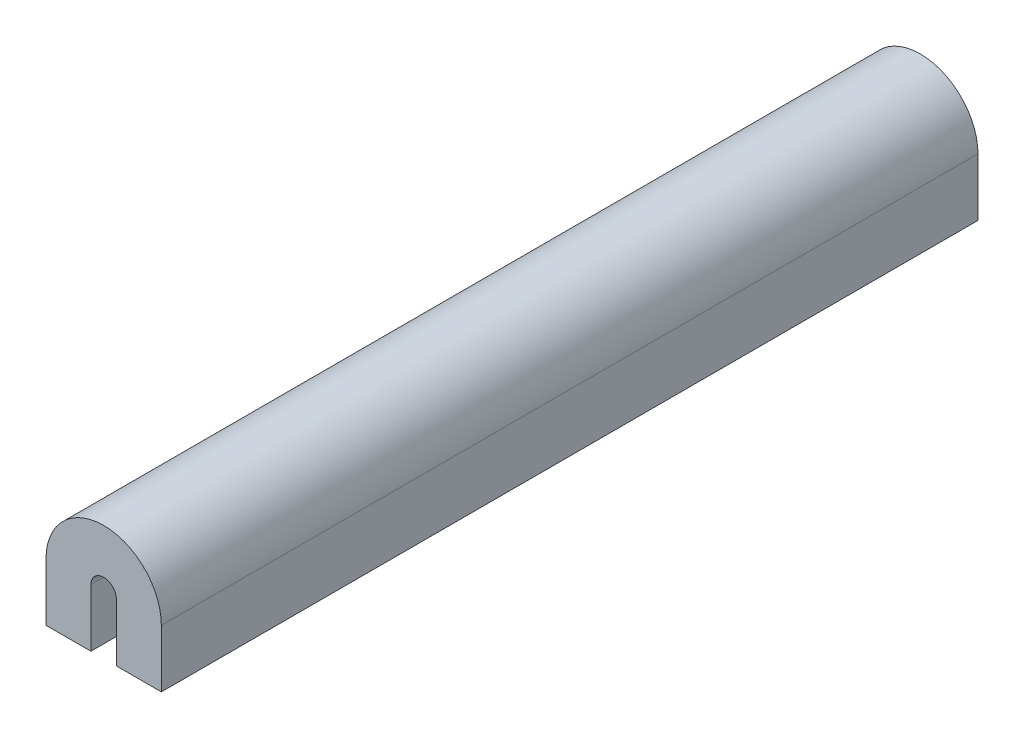
SolidWorks part; units mm, degrees
material "Rubber"
ref_plane "Front" through (0, 0, 0) normal (0, 0, 1) x (1, 0, 0)
ref_plane "Top" through (0, 0, 0) normal (0, 1, 0) x (1, 0, 0)
ref_plane "Right" through (0, 0, 0) normal (1, 0, 0) x (0, 0, -1)
sketch "Sketch1" plane through (0, 0, 0) normal (0, 0, 1) x (1, 0, 0)
  line L0 (0, 0) -> (0, -6.2164) construction
  line L1 (-1.5875, 0) -> (-1.5875, -7.1755)
  line L2 (1.5875, 0) -> (1.5875, -7.1755)
  line L4 (-7.1755, 0) -> (-7.1755, -7.1755)
  line L5 (-7.1755, -7.1755) -> (-1.5875, -7.1755)
  line L7 (7.1755, 0) -> (7.1755, -7.1755)
  line L8 (7.1755, -7.1755) -> (1.5875, -7.1755)
  line L9 (0, 0) -> (0, -7.1755) construction
  arc A0 (7.1755, 0) -> (-7.1755, 0) centre (0, 0) ccw
  arc A1 (1.5875, 0) -> (-1.5875, 0) centre (0, 0) ccw
  point P1 (0, -6.2164)
  point P13 (-1.5875, -7.9375)
  point P14 (0, 0)
  point P15 (-1.5875, -6.2164)
  dimension "D2" = 5.588
  dimension "D1" = 1.5875
extrude "Boss-Extrude1" add sketch "Sketch1" along normal blind 101.6
